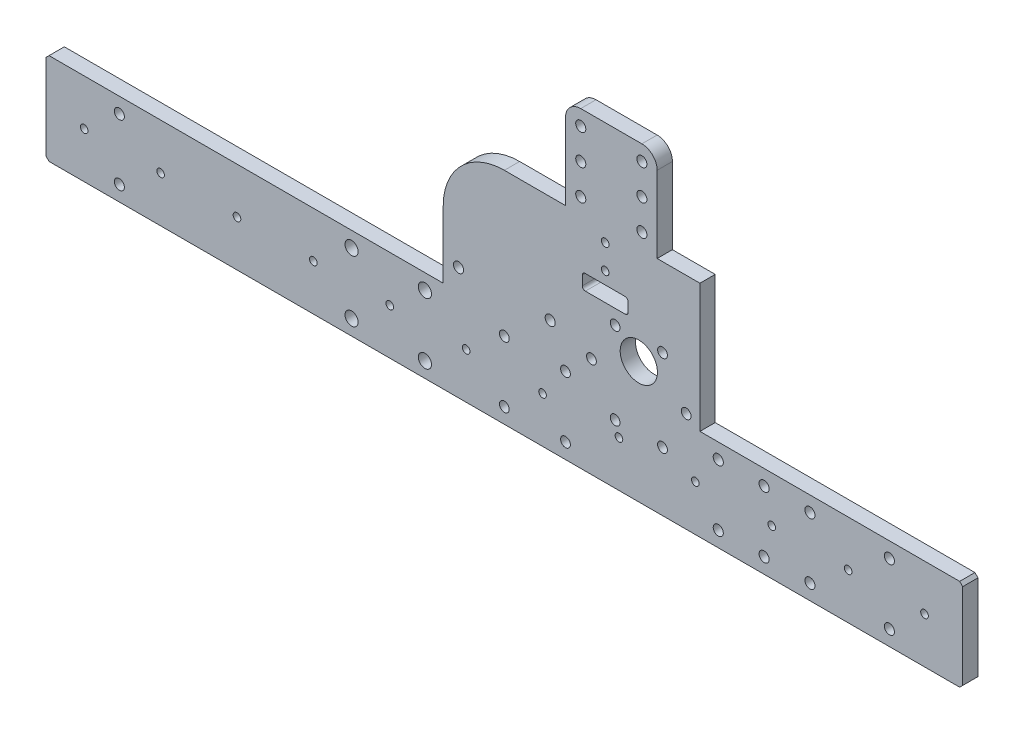
SolidWorks part; units mm, degrees
material "5052-O"
ref_plane "前基準面" through (0, 0, 0) normal (0, 0, 1) x (1, 0, 0)
ref_plane "上基準面" through (0, 0, 0) normal (0, 1, 0) x (1, 0, 0)
ref_plane "右基準面" through (0, 0, 0) normal (1, 0, 0) x (0, 0, -1)
sketch "草圖1" plane through (0, 0, 0) normal (0, 0, 1) x (1, 0, 0)
  line L1 (-150, -15) -> (150, -15)
  line L2 (-150, -15) -> (-150, 15)
  line L3 (-150, 15) -> (150, 15)
  line L4 (150, -15) -> (150, 15)
  line L5 (-150, -15) -> (150, 15) construction
  line L6 (-150, 15) -> (150, -15) construction
  point P0 (0, 0)
  dimension "D1" = 300
  dimension "D2" = 30
extrude "填料-伸長1" add sketch "草圖1" along normal blind 5
chamfer "導角1" distance 1 angle 45 4 edges at (150, -15, 2.5) (150, 15, 2.5) (-150, -15, 2.5) (-150, 15, 2.5)
hole_wizard "M3 餘隙孔1" positions "草圖7" profile "草圖8" hole size "M3" standard "Ansi Metric" end condition through all
sketch "草圖7" plane through (0, 0, 5) normal (0, 0, 1) x (1, 0, 0)
  line L0 (0, 0) -> (10, 0) construction
  line L4 (0, -10) -> (20, -10) construction
  line L5 (0, -10) -> (0, 10) construction
  line L6 (0, 10) -> (20, 10) construction
  line L7 (20, -10) -> (20, 10) construction
  line L8 (0, -10) -> (20, 10) construction
  line L9 (0, 10) -> (20, -10) construction
  point P9 (20, 10)
  point P60 (0, -10)
  point P61 (0, 10)
  point P62 (20, -10)
  dimension "D1" = 10
  dimension "D2" = 20
  dimension "D3" = 20
sketch "草圖8" plane through (20, -10, 5) normal (1, 0, 0) x (0, -1, 0)
  line L0 (0, 0) -> (0, 5)
  line L1 (0, 5) -> (1.6, 5)
  line L2 (1.6, 5) -> (1.6, 0)
  line L5 (1.6, 0) -> (0, 0)
  line L11 (0, -6.35) -> (0, 107.95) construction
  dimension "貫穿孔直徑" = 3.2
  dimension "貫穿孔深度" = 5
hole_wizard "M3x0.5 螺紋孔1" positions "草圖3" profile "草圖4" tap size "M3x0.5" standard "Ansi Metric" end condition through all
sketch "草圖3" plane through (0, 0, 5) normal (0, 0, 1) x (1, 0, 0)
  line L0 (-12.5, 0) -> (12.5, 0) construction
  point P0 (-12.5, 0)
  dimension "D1" = 25
sketch "草圖4" plane through (-12.5, 0, 5) normal (1, 0, 0) x (0, -1, 0)
  line L0 (0, 0) -> (0, 5)
  line L1 (0, 5) -> (1.25, 5)
  line L2 (1.25, 5) -> (1.25, 0)
  line L5 (1.25, 0) -> (0, 0)
  line L11 (0, -6.35) -> (0, 107.95) construction
  dimension "貫穿螺孔鑽直徑" = 2.5
  dimension "貫穿螺孔鑽深度" = 5
hole_wizard "M4x0.7 螺紋孔1" positions "草圖9" profile "草圖10" tap size "M4x0.7" standard "Ansi Metric" end condition through all
sketch "草圖9" plane through (0, 0, 5) normal (0, 0, 1) x (1, 0, 0)
  line L1 (70, -10) -> (100, -10) construction
  line L2 (70, -10) -> (70, 10) construction
  line L3 (70, 10) -> (100, 10) construction
  line L4 (100, -10) -> (100, 10) construction
  line L5 (70, -10) -> (100, 10) construction
  line L6 (70, 10) -> (100, -10) construction
  line L7 (0, 0) -> (85, 0) construction
  point P2 (100, 10)
  point P55 (70, -10)
  point P56 (70, 10)
  point P57 (100, -10)
  point P68 (85, 0)
  point P78 (85, 10)
  point P80 (85, -10)
  dimension "D1" = 30
  dimension "D2" = 20
  dimension "D3" = 85
sketch "草圖10" plane through (100, 10, 5) normal (1, 0, 0) x (0, -1, 0)
  line L0 (0, 0) -> (0, 5)
  line L1 (0, 5) -> (1.65, 5)
  line L2 (1.65, 5) -> (1.65, 0)
  line L5 (1.65, 0) -> (0, 0)
  line L11 (0, -6.35) -> (0, 107.95) construction
  dimension "砮 脸ふ苝 畖" = 3.3
  dimension "砮 脸ふ苝瞏 " = 5
hole_wizard "M4x0.7 螺紋孔2" positions "草圖11" profile "草圖12" tap size "M4x0.7" standard "Ansi Metric" end condition through all
sketch "草圖11" plane through (0, 0, 5) normal (0, 0, 1) x (1, 0, 0)
  line L0 (-150, 0) -> (-126, 0) construction
  line L1 (-150, 14) -> (-150, -14) construction
  line L4 (-126, -10) -> (-126, 10) construction
  point P9 (-126, -10)
  point P10 (-126, 10)
  dimension "D1" = 20
  dimension "D2" = 24
sketch "草圖12" plane through (-126, 10, 5) normal (1, 0, 0) x (0, -1, 0)
  line L0 (0, 0) -> (0, 5)
  line L1 (0, 5) -> (1.65, 5)
  line L2 (1.65, 5) -> (1.65, 0)
  line L5 (1.65, 0) -> (0, 0)
  line L11 (0, -6.35) -> (0, 107.95) construction
  dimension "貫穿螺孔鑽直徑" = 3.3
  dimension "貫穿螺孔鑽深度" = 5
pattern_linear "直線複製排列1" count 6 spacing 25 along (-1, 0, 0) count 7 spacing 25 along (1, 0, 0) of "M3x0.5 螺紋孔1"
mirror "鏡射1" about plane through (0, 0, 0) normal (1, 0, 0) of "M4x0.7 螺紋孔2"
sketch "草圖16" plane through (0, 0, 0) normal (0, 0, 1) x (1, 0, 0)
  line L0 (-20, 15) -> (64, 15)
  line L1 (149, 15) -> (-149, 15) construction
  line L4 (-20, 37) -> (-20, 15)
  line L5 (0, 0) -> (0, 57) construction
  line L9 (64, 15) -> (64, 57)
  line L10 (64, 57) -> (0, 57)
  arc A1 (-20, 37) -> (0, 57) centre (0, 37) cw
  dimension "D3" = 22
  dimension "D1" = 20
  dimension "D2" = 57
  dimension "D4" = 64
extrude "填料-伸長3" add sketch "草圖16" along normal through all
sketch "草圖13" plane through (0, 0, 0) normal (0, 0, 1) x (1, 0, 0)
  circle A1 centre (44, 24.8) radius 6.1
  dimension "D1" = 11.9701
  dimension "D2" = 12.2
  dimension "D3" = 24.8
  dimension "D4" = 44
  dimension "D5" = 34
extrude "除料-伸長2" cut sketch "草圖13" along normal through all
hole_wizard "M2 餘隙孔1" positions "草圖14" profile "草圖15" hole size "M2" standard "Ansi Metric" end condition through all
sketch "草圖14" plane through (0, 0, 5) normal (0, 0, 1) x (1, 0, 0)
  line L1 (39, 24.8) -> (49, 24.8) construction
  circle A2 centre (44, 24.8) radius 6.1 construction
  point P1 (39, 24.8)
  point P2 (49, 24.8)
  point P17 (44, 24.8)
  dimension "D1" = 10
sketch "草圖15" plane through (39, 24.8, 5) normal (1, 0, 0) x (0, -1, 0)
  line L0 (0, 0) -> (0, 5)
  line L1 (0, 5) -> (1.1, 5)
  line L2 (1.1, 5) -> (1.1, 0)
  line L5 (1.1, 0) -> (0, 0)
  line L11 (0, -6.35) -> (0, 107.95) construction
  dimension "貫穿孔直徑" = 2.2
  dimension "貫穿孔深度" = 5
hole_wizard "M4x0.7 螺紋孔3" positions "草圖19" profile "草圖20" tap size "M4x0.7" standard "Ansi Metric" end condition through all
sketch "草圖19" plane through (0, 0, 5) normal (0, 0, 1) x (1, 0, 0)
  line L0 (0, 57) -> (0, 22) construction
  line L4 (-15, 22) -> (15, 22) construction
  point P9 (-15, 22)
  point P10 (15, 22)
  dimension "D1" = 30
  dimension "D2" = 22
sketch "草圖20" plane through (15, 22, 5) normal (1, 0, 0) x (0, -1, 0)
  line L0 (0, 0) -> (0, 5)
  line L1 (0, 5) -> (1.65, 5)
  line L2 (1.65, 5) -> (1.65, 0)
  line L5 (1.65, 0) -> (0, 0)
  line L11 (0, -6.35) -> (0, 107.95) construction
  dimension "貫穿螺孔鑽直徑" = 3.3
  dimension "貫穿螺孔鑽深度" = 5
hole_wizard "M4 餘隙孔1" positions "草圖21" profile "草圖22" hole size "M4" standard "Ansi Metric" end condition through all
sketch "草圖21" plane through (0, 0, 5) normal (0, 0, 1) x (1, 0, 0)
  line L0 (0, 0) -> (-38, 0) construction
  line L4 (-50, -10) -> (-26, -10) construction
  line L5 (-50, -10) -> (-50, 10) construction
  line L6 (-50, 10) -> (-26, 10) construction
  line L7 (-26, -10) -> (-26, 10) construction
  line L8 (-50, -10) -> (-26, 10) construction
  line L9 (-50, 10) -> (-26, -10) construction
  point P11 (-26, 10)
  point P60 (-50, -10)
  point P61 (-50, 10)
  point P62 (-26, -10)
  dimension "D1" = 38
  dimension "D2" = 24
  dimension "D3" = 20
sketch "草圖22" plane through (-26, -10, 5) normal (1, 0, 0) x (0, -1, 0)
  line L0 (0, 0) -> (0, 5)
  line L1 (0, 5) -> (2.15, 5)
  line L2 (2.15, 5) -> (2.15, 0)
  line L5 (2.15, 0) -> (0, 0)
  line L11 (0, -6.35) -> (0, 107.95) construction
  dimension "貫穿孔直徑" = 4.3
  dimension "貫穿孔深度" = 5
hole_wizard "M3x0.5 螺紋孔2" positions "草圖23" profile "草圖24" tap size "M3x0.5" standard "Ansi Metric" end condition through all
sketch "草圖23" plane through (0, 0, 5) normal (0, 0, 1) x (1, 0, 0)
  line L0 (33, 53) -> (33, 45) construction
  line L3 (64, 15) -> (64, 57) construction
  line L4 (64, 57) -> (0, 57) construction
  point P0 (33, 53)
  point P1 (33, 45)
  dimension "D1" = 31
  dimension "D2" = 8
  dimension "D3" = 4
sketch "草圖24" plane through (33, 53, 5) normal (1, 0, 0) x (0, -1, 0)
  line L0 (0, 0) -> (0, 5)
  line L1 (0, 5) -> (1.25, 5)
  line L2 (1.25, 5) -> (1.25, 0)
  line L5 (1.25, 0) -> (0, 0)
  line L11 (0, -6.35) -> (0, 107.95) construction
  dimension "貫穿螺孔鑽直徑" = 2.5
  dimension "貫穿螺孔鑽深度" = 5
sketch "草圖25" plane through (0, 0, 5) normal (0, 0, 1) x (1, 0, 0)
  line L0 (64, 15) -> (64, 57) construction
  line L1 (40.5, 41) -> (25.5, 41)
  line L2 (40.5, 41) -> (40.5, 36)
  line L3 (40.5, 36) -> (25.5, 36)
  line L4 (25.5, 41) -> (25.5, 36)
  line L5 (64, 57) -> (0, 57) construction
  dimension "D1" = 15
  dimension "D2" = 5
  dimension "D3" = 23.5
  dimension "D4" = 16
extrude "除料-伸長3" cut sketch "草圖25" against normal through all and the other way through all
fillet "圓角1" radius 1 4 edges at (40.5, 36, 2.5) (40.5, 41, 2.5) (25.5, 41, 2.5) (25.5, 36, 2.5)
sketch "草圖26" plane through (0, 57, 0) normal (0, 1, 0) x (1, 0, 0)
  line L0 (64, -5) -> (0, -5) construction
  line L1 (50, 0) -> (20, 0)
  line L2 (50, 0) -> (50, -5)
  line L3 (50, -5) -> (20, -5)
  line L4 (20, 0) -> (20, -5)
  line L5 (64, 0) -> (0, 0) construction
  line L6 (64, -5) -> (64, 0) construction
  dimension "D1" = 30
  dimension "D2" = 14
extrude "填料-伸長4" add sketch "草圖26" along normal blind 30
sketch "草圖27" plane through (0, 0, 5) normal (0, 0, 1) x (1, 0, 0)
  line L0 (20, 87) -> (50, 87) construction
  line L1 (20, 87) -> (20, 57) construction
  circle A0 centre (25, 82) radius 1.65
  dimension "D1" = 3.3
  dimension "D2" = 5
  dimension "D3" = 5
extrude "除料-伸長4" cut sketch "草圖27" against normal through all
pattern_linear "直線複製排列2" count 2 spacing 20 along (1, 0, 0) count 3 spacing 10 along (0, -1, 0) of "除料-伸長4"
fillet "圓角2" radius 5 2 edges at (50, 87, 2.5) (20, 87, 2.5)
hole_wizard "M3 餘隙孔2" positions "草圖31" profile "草圖32" hole size "M3" standard "Ansi Metric" end condition through all
sketch "草圖31" plane through (0, 0, 5) normal (0, 0, 1) x (1, 0, 0)
  line L2 (44, 24.8) -> (44, 17.8) construction
  line L3 (28.5, 17.8) -> (59.5, 17.8) construction
  line L6 (36.25, 31.2234) -> (51.75, 4.3766) construction
  line L11 (51.75, 31.2234) -> (36.25, 4.3766) construction
  circle A0 centre (44, 17.8) radius 15.5 construction
  point P13 (28.5, 17.8)
  point P17 (59.5, 17.8)
  point P21 (36.25, 31.2234)
  point P22 (51.75, 4.3766)
  point P29 (51.75, 31.2234)
  point P30 (36.25, 4.3766)
  dimension "D2" = 31
  dimension "D1" = 7
  dimension "D3" = 60
  dimension "D4" = 60
sketch "草圖32" plane through (36.25, 4.3766, 5) normal (1, 0, 0) x (0, -1, 0)
  line L0 (0, 0) -> (0, 5)
  line L1 (0, 5) -> (1.6, 5)
  line L2 (1.6, 5) -> (1.6, 0)
  line L5 (1.6, 0) -> (0, 0)
  line L11 (0, -6.35) -> (0, 107.95) construction
  dimension "貫穿孔直徑" = 3.2
  dimension "貫穿孔深度" = 5
